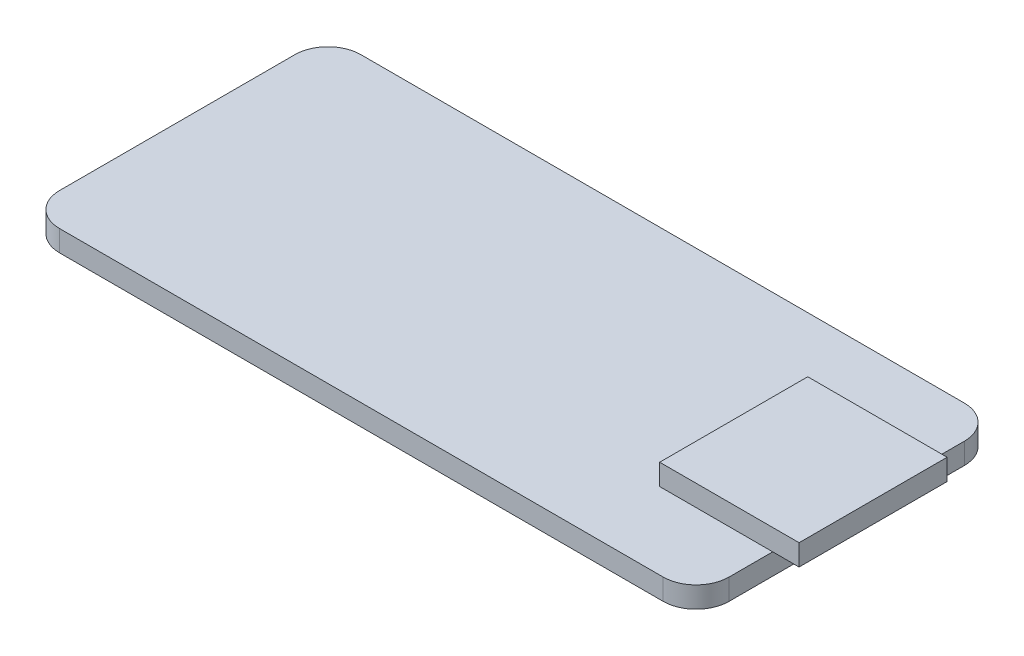
SolidWorks part; units mm, degrees
ref_plane "Front Plane" through (0, 0, 0) normal (0, 0, 1) x (1, 0, 0)
ref_plane "Top Plane" through (0, 0, 0) normal (0, 1, 0) x (1, 0, 0)
ref_plane "Right Plane" through (0, 0, 0) normal (1, 0, 0) x (0, 0, -1)
sketch "Sketch1" plane through (0, 0, 0) normal (0, 1, 0) x (1, 0, 0)
  line L1 (-22.9, 11.43) -> (22.9, 11.43)
  line L2 (-25.4, 8.93) -> (-25.4, -8.93)
  line L3 (-22.9, -11.43) -> (22.9, -11.43)
  line L4 (25.4, 8.93) -> (25.4, -8.93)
  line L5 (-25.4, 11.43) -> (25.4, -11.43) construction
  line L6 (-25.4, -11.43) -> (25.4, 11.43) construction
  arc A0 (22.9, 11.43) -> (25.4, 8.93) centre (22.9, 8.93) cw
  arc A1 (22.9, -11.43) -> (25.4, -8.93) centre (22.9, -8.93) ccw
  arc A2 (-25.4, -8.93) -> (-22.9, -11.43) centre (-22.9, -8.93) ccw
  arc A3 (-22.9, 11.43) -> (-25.4, 8.93) centre (-22.9, 8.93) ccw
  point P0 (0, 0)
  dimension "D3" = 2.5
  dimension "D1" = 22.86
  dimension "D2" = 50.8
extrude "Boss-Extrude1" add sketch "Sketch1" along normal blind 1.6
sketch "Sketch2" plane through (0, 1.6, 0) normal (0, 1, 0) x (1, 0, 0)
  line L0 (-22.9, -11.43) -> (22.9, -11.43) construction
  line L1 (27.4, 5.6163) -> (16.8227, 5.6163)
  line L2 (27.4, 5.6163) -> (27.4, -5.6163)
  line L3 (27.4, -5.6163) -> (16.8227, -5.6163)
  line L4 (16.8227, 5.6163) -> (16.8227, -5.6163)
  line L5 (27.4, 5.6163) -> (16.8227, -5.6163) construction
  line L6 (27.4, -5.6163) -> (16.8227, 5.6163) construction
  line L7 (25.4, -8.93) -> (25.4, 8.93) construction
  point P0 (22.1114, 0)
  dimension "D1" = 11.43
  dimension "D2" = 2
extrude "Boss-Extrude2" add sketch "Sketch2" along normal blind 1.6
